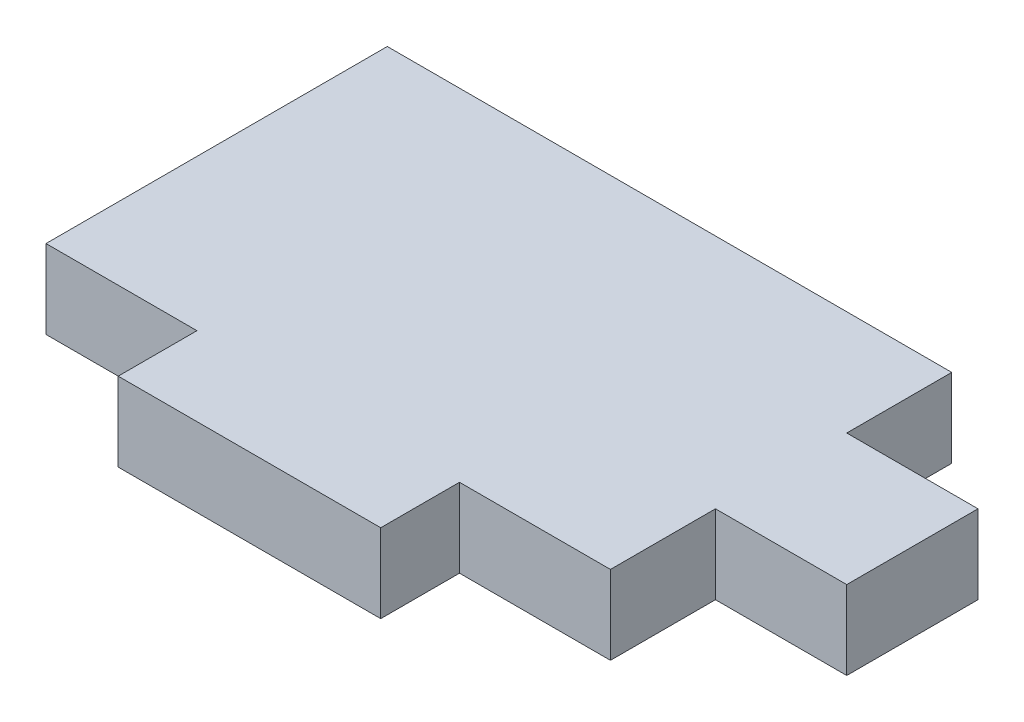
SolidWorks part; units mm, degrees
ref_plane "Front Plane" through (0, 0, 0) normal (0, 0, 1) x (1, 0, 0)
ref_plane "Top Plane" through (0, 0, 0) normal (0, 1, 0) x (1, 0, 0)
ref_plane "Right Plane" through (0, 0, 0) normal (1, 0, 0) x (0, 0, -1)
sketch "Sketch1" plane through (0, 0, 0) normal (0, 1, 0) x (1, 0, 0)
  line L0 (-15.75, 0) -> (-15.75, -3)
  line L1 (-21.5, 13) -> (0, 13)
  line L2 (-21.5, 13) -> (-21.5, 0)
  line L3 (-21.5, 0) -> (-15.75, 0)
  line L4 (0, 13) -> (0, 9)
  line L5 (-15.75, -3) -> (-5.75, -3)
  line L6 (-5.75, -3) -> (-5.75, 0)
  line L7 (-5.75, 0) -> (0, 0)
  line L8 (0, 9) -> (5, 9)
  line L9 (5, 9) -> (5, 4)
  line L10 (5, 4) -> (0, 4)
  line L11 (0, 4) -> (0, 0)
  point P5 (-15.75, 0)
  point P11 (0, 9)
  point P15 (0, 0)
  dimension "D1" = 21.5
  dimension "D2" = 13
  dimension "D3" = 5.75
  dimension "D4" = 10
  dimension "D5" = 3
  dimension "D6" = 4
  dimension "D7" = 5
  dimension "D8" = 5
extrude "Boss-Extrude1" add sketch "Sketch1" along normal blind 3
